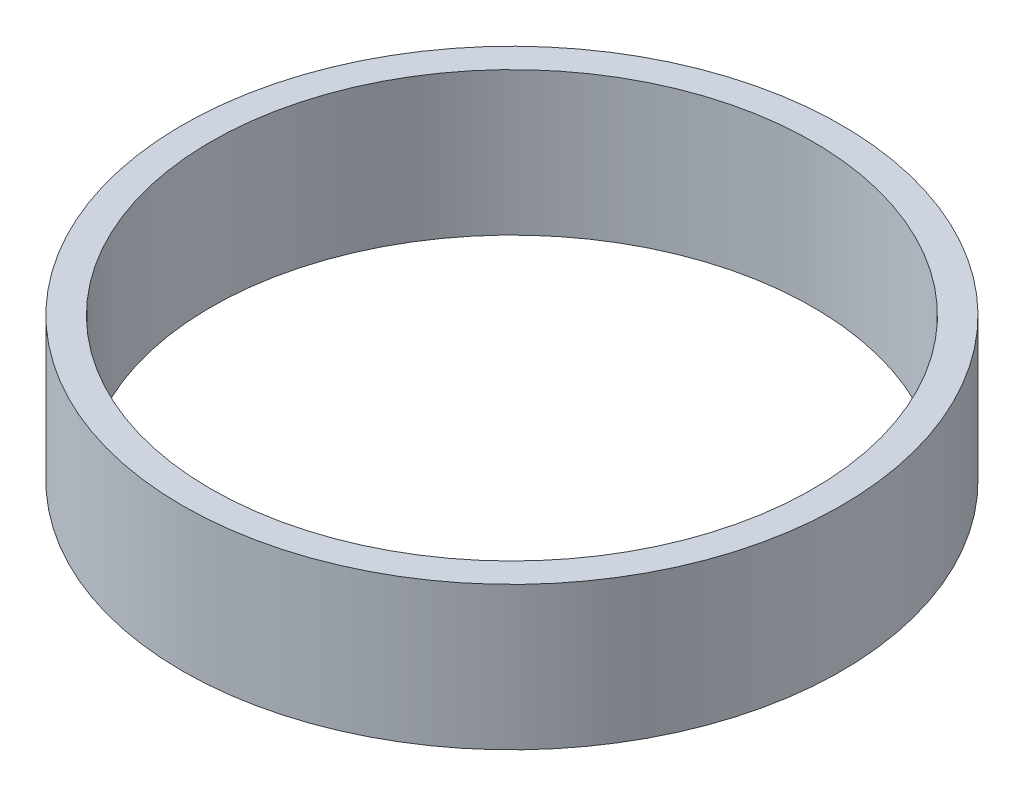
SolidWorks part; units mm, degrees
ref_plane "Front Plane" through (0, 0, 0) normal (0, 0, 1) x (1, 0, 0)
ref_plane "Top Plane" through (0, 0, 0) normal (0, 1, 0) x (1, 0, 0)
ref_plane "Right Plane" through (0, 0, 0) normal (1, 0, 0) x (0, 0, -1)
sketch "Sketch1" plane through (0, 0, 0) normal (0, 1, 0) x (1, 0, 0)
  circle A0 centre (0, 0) radius 23
  circle A1 centre (0, 0) radius 21
  dimension "D1" = 42
  dimension "D2" = 46
extrude "Boss-Extrude1" add sketch "Sketch1" along normal blind 10
